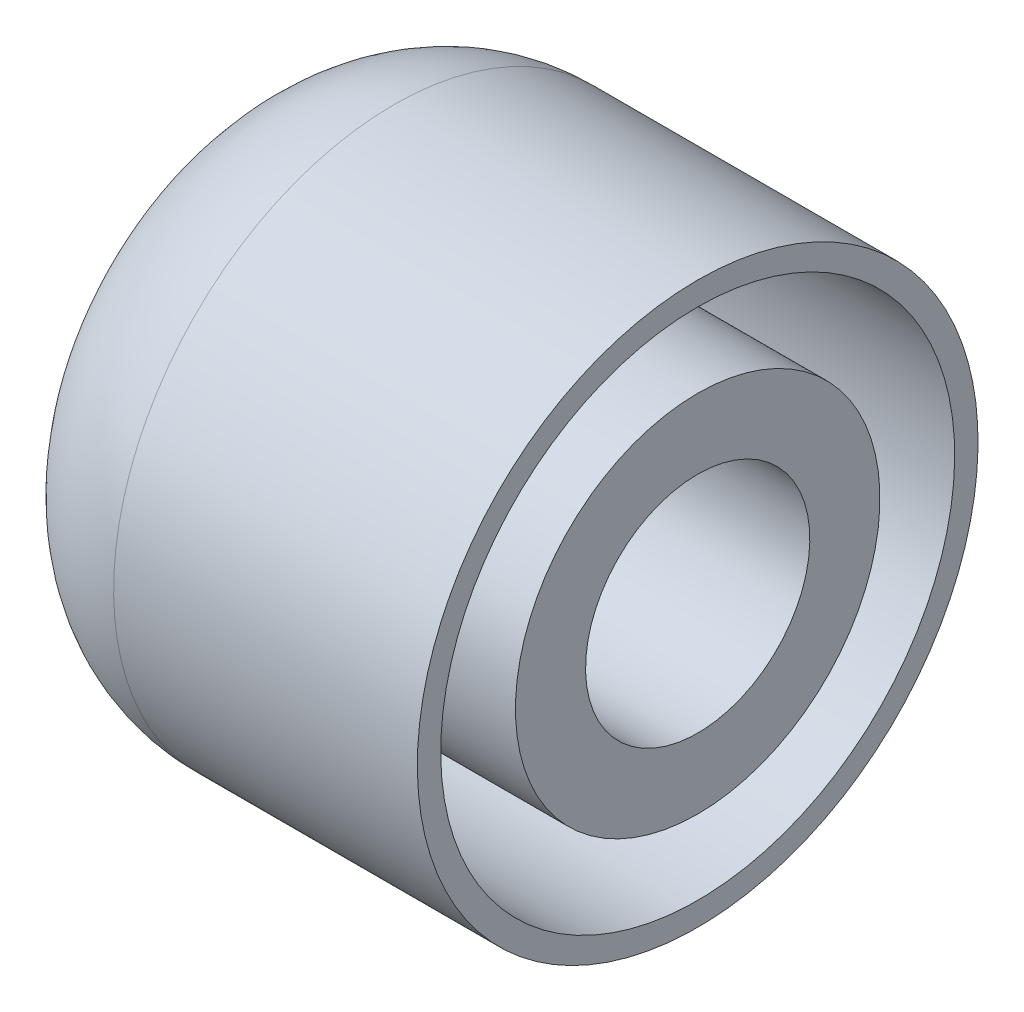
SolidWorks part; units mm, degrees
ref_plane "Front" through (0, 0, 0) normal (0, 0, 1) x (1, 0, 0)
ref_plane "Top" through (0, 0, 0) normal (0, 1, 0) x (1, 0, 0)
ref_plane "Right" through (0, 0, 0) normal (1, 0, 0) x (0, 0, -1)
sketch "Sketch1" plane through (0, 0, 0) normal (0, 0, 1) x (1, 0, 0)
  line L0 (0, 0) -> (-10, 0) construction
  line L1 (0, 2.4) -> (-10, 2.4)
  line L2 (-10, 2.4) -> (-10, 2.5)
  line L3 (-6.5, 6) -> (0, 6)
  line L4 (0, 6) -> (0, 5.5)
  line L5 (0, 5.5) -> (-6, 5.5)
  line L6 (-6, 5.5) -> (-6, 3.9)
  line L7 (-6, 3.9) -> (0, 3.9)
  line L8 (0, 3.9) -> (0, 2.4)
  arc A0 (-10, 2.5) -> (-6.5, 6) centre (-6.5, 2.5) cw
  dimension "D7" = 3.5
  dimension "D1" = 4.8
  dimension "D2" = 10
  dimension "D3" = 11
  dimension "D4" = 7.8
  dimension "D5" = 12
  dimension "D6" = 6
revolve "Revolve1" add sketch "Sketch1" angle 360 about L0
